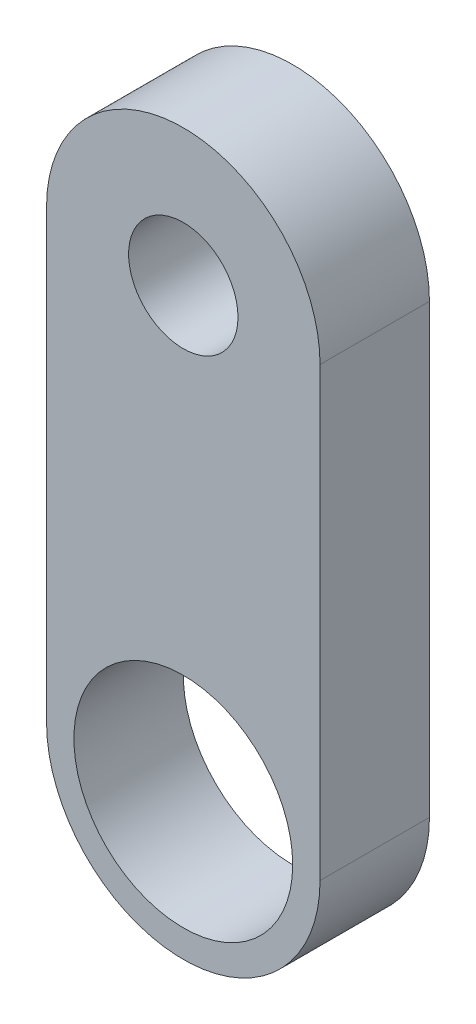
SolidWorks part; units mm, degrees
ref_plane "정면" through (0, 0, 0) normal (0, 0, 1) x (1, 0, 0)
ref_plane "윗면" through (0, 0, 0) normal (0, 1, 0) x (1, 0, 0)
ref_plane "우측면" through (0, 0, 0) normal (1, 0, 0) x (0, 0, -1)
sketch "스케치1" plane through (0, 0, 0) normal (0, 0, 1) x (1, 0, 0)
  line L2 (-2.5, 4.085) -> (-2.5, -4.085)
  line L4 (2.5, 4.085) -> (2.5, -4.085)
  line L5 (-2.5, 4.085) -> (2.5, -4.085) construction
  line L6 (-2.5, -4.085) -> (2.5, 4.085) construction
  arc A0 (-2.5, 4.085) -> (2.5, 4.085) centre (0, 4.085) cw
  arc A1 (2.5, -4.085) -> (-2.5, -4.085) centre (0, -4.085) cw
  circle A2 centre (0, 4.085) radius 1
  circle A3 centre (0, -4.085) radius 2
  point P0 (0, 0)
  dimension "D1" = 8.17
extrude "보스-돌출1" add sketch "스케치1" along normal blind 2
